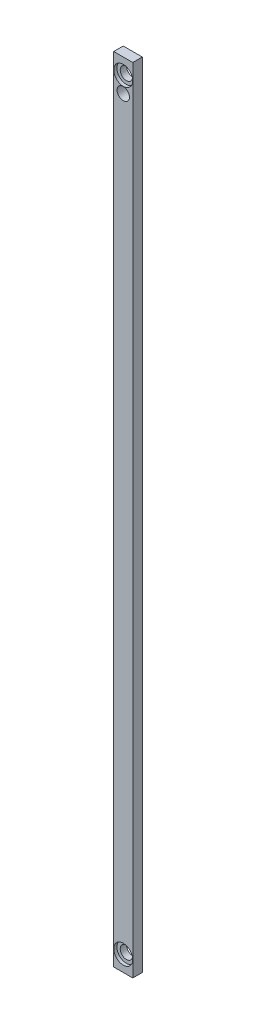
SolidWorks part; units mm, degrees
ref_plane "Plan de face" through (0, 0, 0) normal (0, 0, 1) x (1, 0, 0)
ref_plane "Plan de dessus" through (0, 0, 0) normal (0, 1, 0) x (1, 0, 0)
ref_plane "Plan de droite" through (0, 0, 0) normal (1, 0, 0) x (0, 0, -1)
sketch "Esquisse1" plane through (0, 0, 0) normal (0, 0, 1) x (1, 0, 0)
  line L1 (0, 0) -> (-6, 0)
  line L2 (0, 0) -> (0, 250)
  line L3 (0, 250) -> (-6, 250)
  line L4 (-6, 0) -> (-6, 250)
  dimension "D1" = 250
  dimension "D2" = 6
extrude "Boss.-Extru.1" add sketch "Esquisse1" along normal blind 3
sketch "Esquisse2" plane through (0, 0, 3) normal (0, 0, 1) x (1, 0, 0)
  line L0 (0, 250) -> (-6, 250) construction
  line L2 (-6, 0) -> (0, 0) construction
  circle A0 centre (-3, 245) radius 1.95
  circle A1 centre (-3, 240) radius 1.95
  circle A2 centre (-3, 5) radius 1.95
  point P6 (-3, 0)
  point P10 (-3, 0)
  point P15 (-3, 250)
  dimension "D1" = 3.9
  dimension "D2" = 3.9
  dimension "D3" = 5
  dimension "D5" = 5
  dimension "D7" = 3.9
  dimension "D8" = 5
  dimension "D4" = 0
  dimension "D6" = 0
extrude "Enlèv. mat.-Extru.1" cut sketch "Esquisse2" against normal blind 3
sketch "Esquisse3" plane through (0, 0, 3) normal (0, 0, 1) x (1, 0, 0)
  circle A0 centre (-3, 5) radius 2.995
  circle A1 centre (-3, 245) radius 2.995
  dimension "D1" = 5.99
  dimension "D2" = 5.99
extrude "Enlèv. mat.-Extru.3" cut sketch "Esquisse3" against normal blind 1
